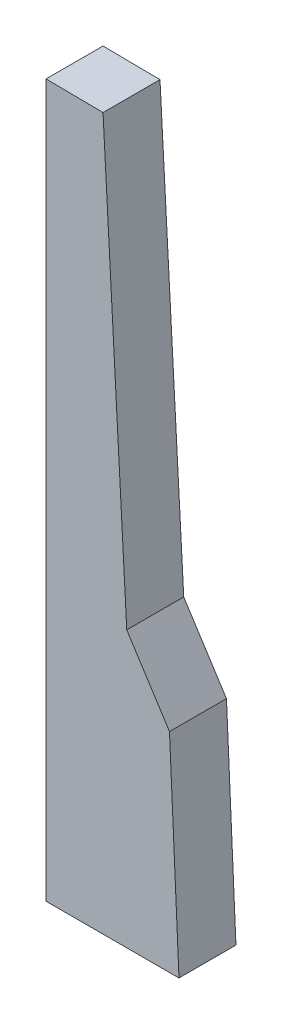
SolidWorks part; units mm, degrees
ref_plane "Front" through (0, 0, 0) normal (0, 0, 1) x (1, 0, 0)
ref_plane "Top" through (0, 0, 0) normal (0, 1, 0) x (1, 0, 0)
ref_plane "Right" through (0, 0, 0) normal (1, 0, 0) x (0, 0, -1)
sketch "Sketch1" plane through (0, 0, 0) normal (0, 0, 1) x (1, 0, 0)
  line L0 (0, 0) -> (0, 75)
  line L1 (0, 75) -> (5.9996, 74.932)
  line L2 (5.9996, 74.932) -> (8.5, 29)
  line L3 (8.5, 29) -> (13, 21.9773)
  line L4 (13, 21.9773) -> (14, 0)
  line L5 (14, 0) -> (0, 0)
  dimension "D1" = 75
  dimension "D2" = 13
  dimension "D3" = 22
  dimension "D4" = 46
  dimension "D5" = 6
  dimension "D6" = 14
  dimension "D7" = 8.5
extrude "Boss-Extrude1" add sketch "Sketch1" along normal blind 6
